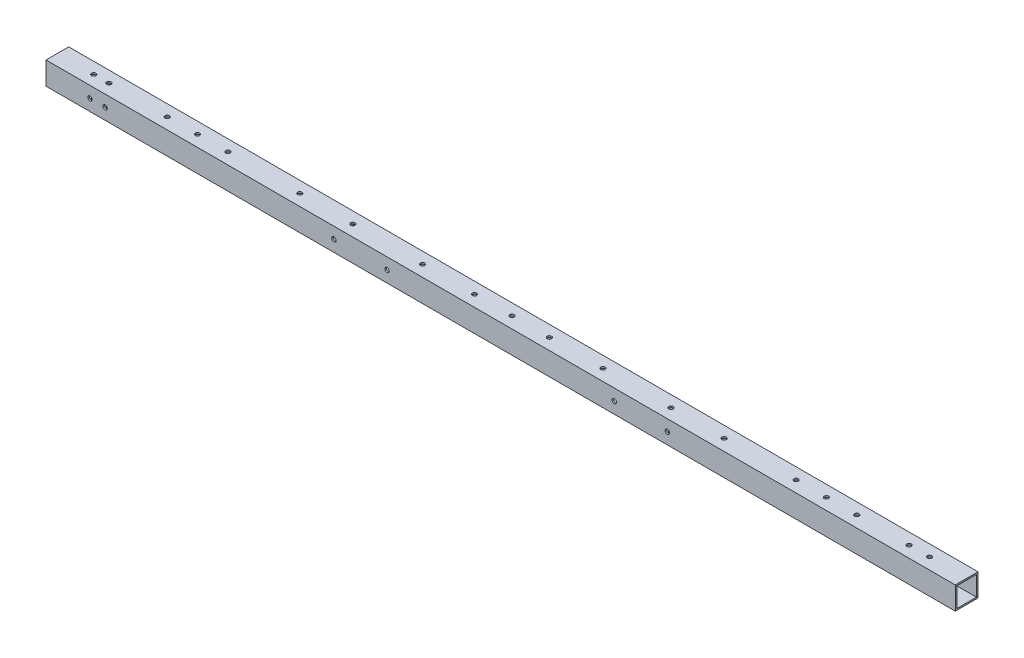
SolidWorks part; units mm, degrees
material "Thornel Mat VMA"
ref_plane "前视基准面" through (0, 0, 0) normal (0, 0, 1) x (1, 0, 0)
ref_plane "上视基准面" through (0, 0, 0) normal (0, 1, 0) x (1, 0, 0)
ref_plane "右视基准面" through (0, 0, 0) normal (1, 0, 0) x (0, 0, -1)
other "Configuration Table"
sketch "草图1" plane through (0, 0, 0) normal (1, 0, 0) x (0, 0, -1)
  line L0 (-6.5, -6.5) -> (-6.5, 6.5)
  line L1 (-7.5, -7.5) -> (7.5, -7.5)
  line L2 (-7.5, -7.5) -> (-7.5, 7.5)
  line L3 (-7.5, 7.5) -> (7.5, 7.5)
  line L4 (7.5, -7.5) -> (7.5, 7.5)
  line L5 (-7.5, -7.5) -> (7.5, 7.5) construction
  line L6 (-7.5, 7.5) -> (7.5, -7.5) construction
  line L7 (-6.5, 6.5) -> (6.5, 6.5)
  line L8 (6.5, -6.5) -> (6.5, 6.5)
  line L9 (-6.5, -6.5) -> (6.5, -6.5)
  point P0 (0, 0)
  dimension "D1" = 15
  dimension "D2" = 15
  dimension "D3" = 1
extrude "凸台-拉伸1" add sketch "草图1" along normal blind 600
sketch "草图2" plane through (0, 7.5, 0) normal (0, 1, 0) x (1, 0, 0)
  line L0 (195, 0) -> (241, 0) construction
  circle A0 centre (487.5, 0) radius 1.45 construction
  circle A1 centre (507.5, 0) radius 1.45 construction
  circle A2 centre (527.5, 0) radius 1.45 construction
  circle A3 centre (72.5, 0) radius 1.45 construction
  circle A4 centre (92.5, 0) radius 1.45 construction
  circle A5 centre (112.5, 0) radius 1.45 construction
  circle A6 centre (34, 0) radius 1.45 construction
  circle A7 centre (160, 0) radius 1.45 construction
  circle A8 centre (195, 0) radius 1.45 construction
  circle A9 centre (275.3, 0) radius 1.45 construction
  circle A10 centre (300, 0) radius 1.45 construction
  circle A11 centre (324.7, 0) radius 1.45 construction
  circle A12 centre (405, 0) radius 1.45 construction
  circle A13 centre (440, 0) radius 1.45 construction
  circle A14 centre (562, 0) radius 1.45 construction
  circle A15 centre (575.5, 0) radius 1.45 construction
  circle A16 centre (487.5, 0) radius 1.45
  circle A17 centre (507.5, 0) radius 1.45
  circle A18 centre (527.5, 0) radius 1.45
  circle A19 centre (72.5, 0) radius 1.45
  circle A20 centre (92.5, 0) radius 1.45
  circle A21 centre (112.5, 0) radius 1.45
  circle A22 centre (34, 0) radius 1.45
  circle A23 centre (160, 0) radius 1.45
  circle A24 centre (195, 0) radius 1.45
  circle A25 centre (275.3, 0) radius 1.45
  circle A26 centre (300, 0) radius 1.45
  circle A27 centre (324.7, 0) radius 1.45
  circle A28 centre (405, 0) radius 1.45
  circle A29 centre (440, 0) radius 1.45
  circle A30 centre (562, 0) radius 1.45
  circle A31 centre (575.5, 0) radius 1.45
  circle A32 centre (24, 0) radius 1.45 construction
  circle A33 centre (24, 0) radius 1.45
  circle A34 centre (360, 0) radius 1.45 construction
  circle A35 centre (360, 0) radius 1.45
  circle A36 centre (241, 0) radius 1.45
  dimension "D1" = 2.9
  dimension "D2" = 46
extrude "切除-拉伸1" cut sketch "草图2" against normal through all
sketch "草图3" plane through (0, 0, -7.5) normal (0, 0, -1) x (-1, 0, 0)
  circle A0 centre (-375, 0) radius 1.45 construction
  circle A1 centre (-410, 0) radius 1.45 construction
  circle A2 centre (-375, 0) radius 1.45
  circle A3 centre (-410, 0) radius 1.45
  circle A4 centre (-29, 0) radius 1.45 construction
  circle A5 centre (-39, 0) radius 1.45 construction
  circle A6 centre (-190, 0) radius 1.45 construction
  circle A7 centre (-225, 0) radius 1.45 construction
  circle A8 centre (-29, 0) radius 1.45
  circle A9 centre (-39, 0) radius 1.45
  circle A10 centre (-190, 0) radius 1.45
  circle A11 centre (-225, 0) radius 1.45
extrude "切除-拉伸2" cut sketch "草图3" against normal through all
